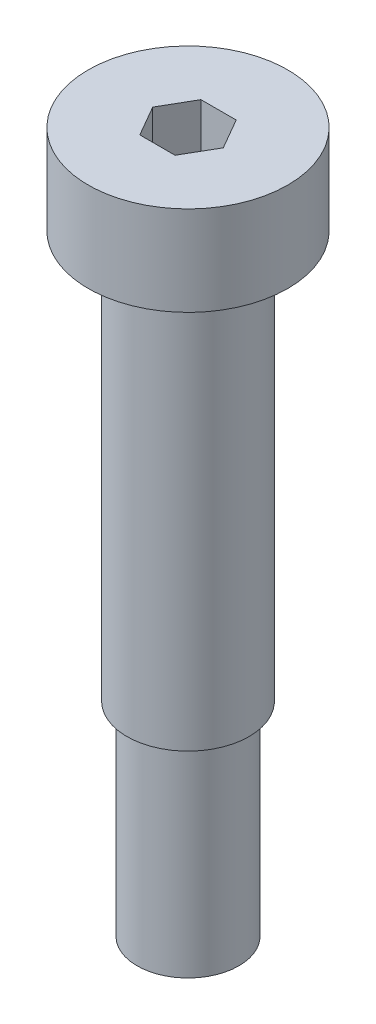
SolidWorks part; units mm, degrees
ref_plane "前视基准面" through (0, 0, 0) normal (0, 0, 1) x (1, 0, 0)
ref_plane "上视基准面" through (0, 0, 0) normal (0, 1, 0) x (1, 0, 0)
ref_plane "右视基准面" through (0, 0, 0) normal (1, 0, 0) x (0, 0, -1)
sketch "草图1" plane through (0, 0, 0) normal (0, 0, 1) x (1, 0, 0)
  line L0 (0, 0) -> (0, 34.4)
  line L1 (0, 34.4) -> (4.9, 34.4)
  line L2 (4.9, 34.4) -> (4.9, 30)
  line L3 (4.9, 30) -> (3, 30)
  line L4 (3, 30) -> (3, 10)
  line L5 (3, 10) -> (2.5, 10)
  line L6 (2.5, 10) -> (2.5, 0)
  line L7 (2.5, 0) -> (0, 0)
  dimension "D1" = 4.4
  dimension "D2" = 4.9
  dimension "D3" = 10
  dimension "D4" = 2.5
  dimension "D5" = 3
  dimension "D6" = 20
revolve "旋转1" add sketch "草图1" angle 360 about L0
cosmetic thread "装饰螺纹线1" parameters "D1"=10, "D2"=4
sketch "草图2" plane through (0, 34.4, 0) normal (0, 1, 0) x (1, 0, 0)
  line L1 (1.7321, 0) -> (0.866, 1.5)
  line L2 (0.866, 1.5) -> (-0.866, 1.5)
  line L3 (-0.866, 1.5) -> (-1.7321, 0)
  line L4 (-1.7321, 0) -> (-0.866, -1.5)
  line L5 (-0.866, -1.5) -> (0.866, -1.5)
  line L6 (0.866, -1.5) -> (1.7321, 0)
  circle A0 centre (0, 0) radius 1.5 construction
  dimension "D1" = 3
extrude "切除-拉伸1" cut sketch "草图2" against normal blind 3
